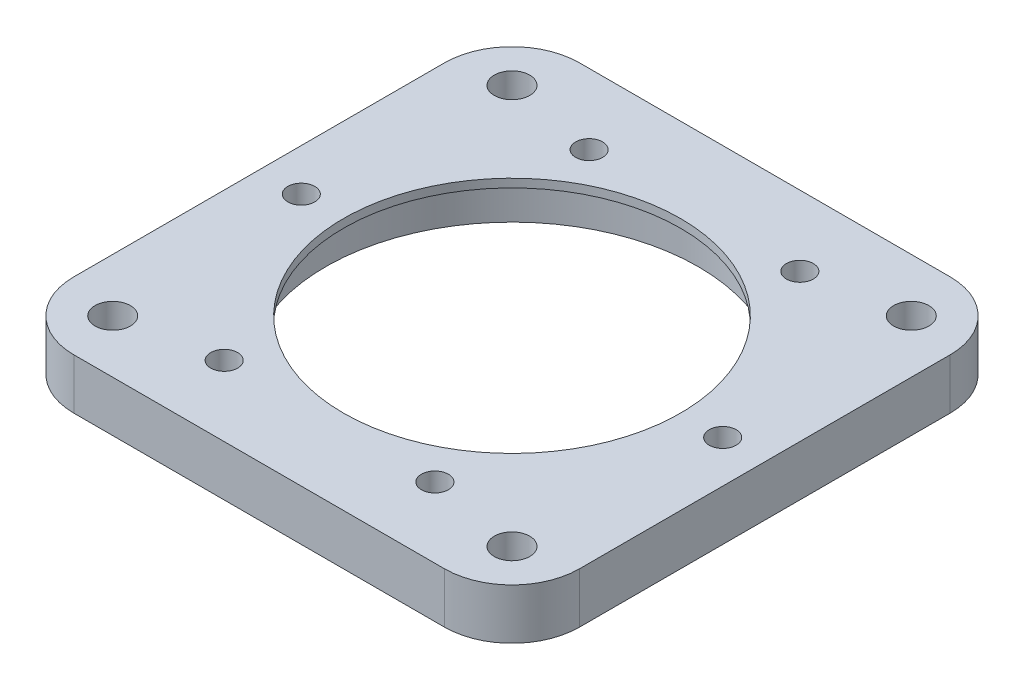
SolidWorks part; units mm, degrees
ref_plane "前视基准面" through (0, 0, 0) normal (0, 0, 1) x (1, 0, 0)
ref_plane "上视基准面" through (0, 0, 0) normal (0, 1, 0) x (1, 0, 0)
ref_plane "右视基准面" through (0, 0, 0) normal (1, 0, 0) x (0, 0, -1)
other "Configuration Table"
sketch "草图1" plane through (0, 0, 0) normal (0, 1, 0) x (1, 0, 0)
  line L1 (-30, -30) -> (30, -30)
  line L2 (-30, -30) -> (-30, 30)
  line L3 (-30, 30) -> (30, 30)
  line L4 (30, -30) -> (30, 30)
  line L5 (-30, -30) -> (30, 30) construction
  line L6 (-30, 30) -> (30, -30) construction
  circle A0 centre (0, 0) radius 20
  point P0 (0, 0)
  dimension "D3" = 40
  dimension "D1" = 60
  dimension "D2" = 60
extrude "凸台-拉伸1" add sketch "草图1" along normal blind 6
sketch "草图3" plane through (0, 0, 0) normal (0, -1, 0) x (1, 0, 0)
  circle A0 centre (0, 0) radius 22.1
  dimension "D1" = 44.2
extrude "切除-拉伸1" cut sketch "草图3" against normal blind 5
sketch "草图4" plane through (0, 6, 0) normal (0, 1, 0) x (1, 0, 0)
  line L0 (0, 0) -> (30, 30) construction
  circle A0 centre (0, 0) radius 25 construction
  circle A1 centre (25, 0) radius 1.6
  circle A2 centre (12.5, -21.6506) radius 1.6
  circle A3 centre (-12.5, -21.6506) radius 1.6
  circle A4 centre (-25, 0) radius 1.6
  circle A5 centre (-12.5, 21.6506) radius 1.6
  circle A6 centre (12.5, 21.6506) radius 1.6
  circle A7 centre (0, 0) radius 33.5 construction
  circle A8 centre (23.6881, 23.6881) radius 2.1
  circle A9 centre (23.6881, -23.6881) radius 2.1
  circle A10 centre (-23.6881, -23.6881) radius 2.1
  circle A11 centre (-23.6881, 23.6881) radius 2.1
  dimension "D1" = 50
  dimension "D2" = 3.2
  dimension "D4" = 67
  dimension "D5" = 4.2
  dimension "D3" = 6
  dimension "D6" = 4
extrude "切除-拉伸2" cut sketch "草图4" against normal blind 6
fillet "圆角1" radius 8 4 edges at (-30, 3, 30) (30, 3, 30) (-30, 3, -30) (30, 3, -30)
